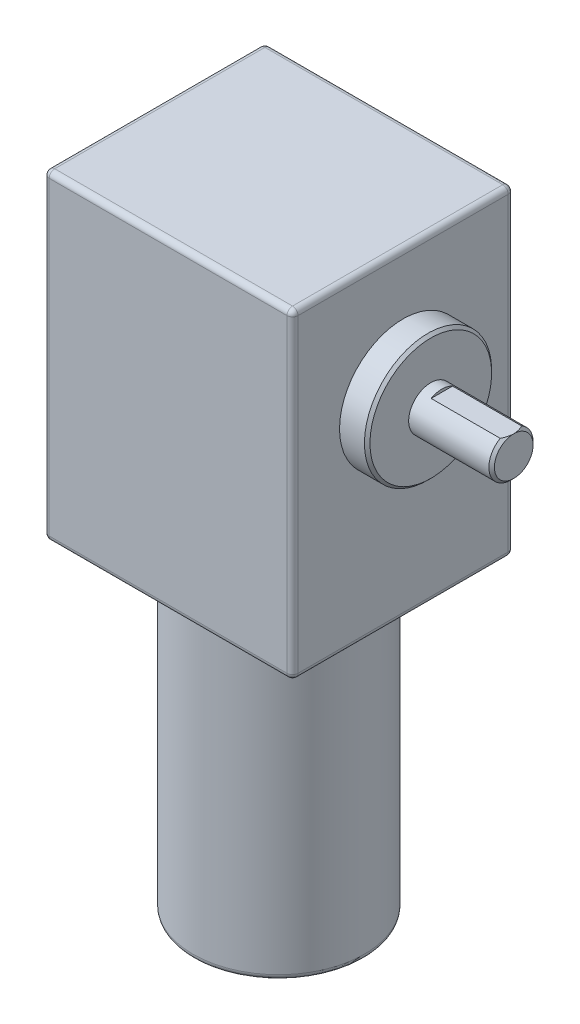
SolidWorks part; units mm, degrees
ref_plane "Front Plane" through (0, 0, 0) normal (0, 0, 1) x (1, 0, 0)
ref_plane "Top Plane" through (0, 0, 0) normal (0, 1, 0) x (1, 0, 0)
ref_plane "Right Plane" through (0, 0, 0) normal (1, 0, 0) x (0, 0, -1)
sketch "Sketch1" plane through (0, 0, 0) normal (1, 0, 0) x (0, 0, -1)
  circle A0 centre (0, 0) radius 4
  dimension "D1" = 8
extrude "Boss-Extrude1" add sketch "Sketch1" along normal blind 15
sketch "Sketch2" plane through (0, 0, 0) normal (-1, 0, 0) x (0, 0, 1)
  circle A0 centre (0, 0) radius 11.5
  dimension "D1" = 23
extrude "Boss-Extrude2" add sketch "Sketch2" along normal blind 5
sketch "Sketch3" plane through (-5, 0, 0) normal (-1, 0, 0) x (0, 0, 1)
  line L0 (0, 11.5) -> (0, 22.5) construction
  line L1 (20, -35.5) -> (-20, -35.5)
  line L2 (20, -35.5) -> (20, 22.5)
  line L3 (20, 22.5) -> (-20, 22.5)
  line L4 (-20, -35.5) -> (-20, 22.5)
  line L5 (20, 0) -> (-20, 0) construction
  circle A0 centre (0, 0) radius 11.5 construction
  dimension "D1" = 40
  dimension "D2" = 58
  dimension "D3" = 11
extrude "Boss-Extrude3" add sketch "Sketch3" along normal blind 45
sketch "Sketch6" plane through (0, -35.5, 0) normal (0, -1, 0) x (1, 0, 0)
  line L0 (-5, -20) -> (-50, 20) construction
  circle A0 centre (-27.5, 0) radius 15.5
  point P6 (0, 0)
  dimension "D1" = 31
extrude "Boss-Extrude4" add sketch "Sketch6" along normal blind 57
chamfer "Chamfer1" distance 0.5 angle 45 2 edges at (0, 0, 11.5) (15, 0, -4)
fillet "Fillet1" radius 1 13 edges at (-50, -35.5, 0) (-5, -35.5, 0) (-50, 22.5, 0) (-5, 22.5, 0) (-27.5, -35.5, 20) (-50, -6.5, 20) (-27.5, 22.5, 20) (-5, -6.5, 20) (-27.5, 22.5, -20) (-50, -6.5, -20) (-27.5, -35.5, -20) (-5, -6.5, -20) (-27.5, -92.5, -15.5)
sketch "Sketch4" plane through (15, 0, 0) normal (1, 0, 0) x (0, 0, -1)
  line L1 (-1.9365, 11) -> (1.9365, 11)
  line L2 (-1.9365, 11) -> (-1.9365, 3.5)
  line L3 (-1.9365, 3.5) -> (1.9365, 3.5)
  line L4 (1.9365, 11) -> (1.9365, 3.5)
  circle A0 centre (0, 0) radius 11 construction
  circle A1 centre (0, 0) radius 4 construction
  point P4 (0, 0)
  point P7 (0, 0)
  dimension "D1" = 3.5
extrude "Cut-Extrude1" cut sketch "Sketch4" against normal blind 13
